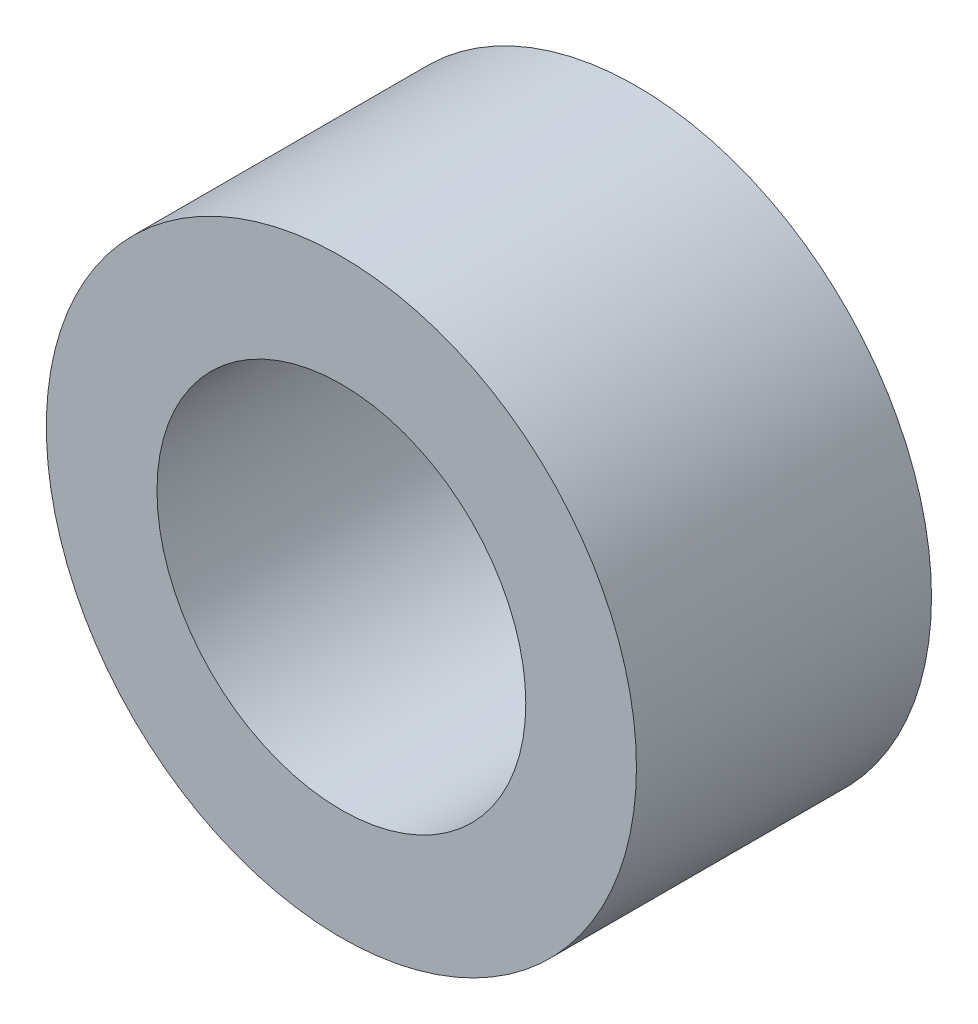
SolidWorks part; units mm, degrees
ref_plane "Front Plane" through (0, 0, 0) normal (0, 0, 1) x (1, 0, 0)
ref_plane "Top Plane" through (0, 0, 0) normal (0, 1, 0) x (1, 0, 0)
ref_plane "Right Plane" through (0, 0, 0) normal (1, 0, 0) x (0, 0, -1)
sketch "Sketch1" plane through (0, 0, 0) normal (0, 0, 1) x (1, 0, 0)
  circle A0 centre (0, 0) radius 3.125
  circle A1 centre (0, 0) radius 5
  dimension "D1" = 10
  dimension "D2" = 6.25
extrude "Boss-Extrude1" add sketch "Sketch1" along normal blind 5
